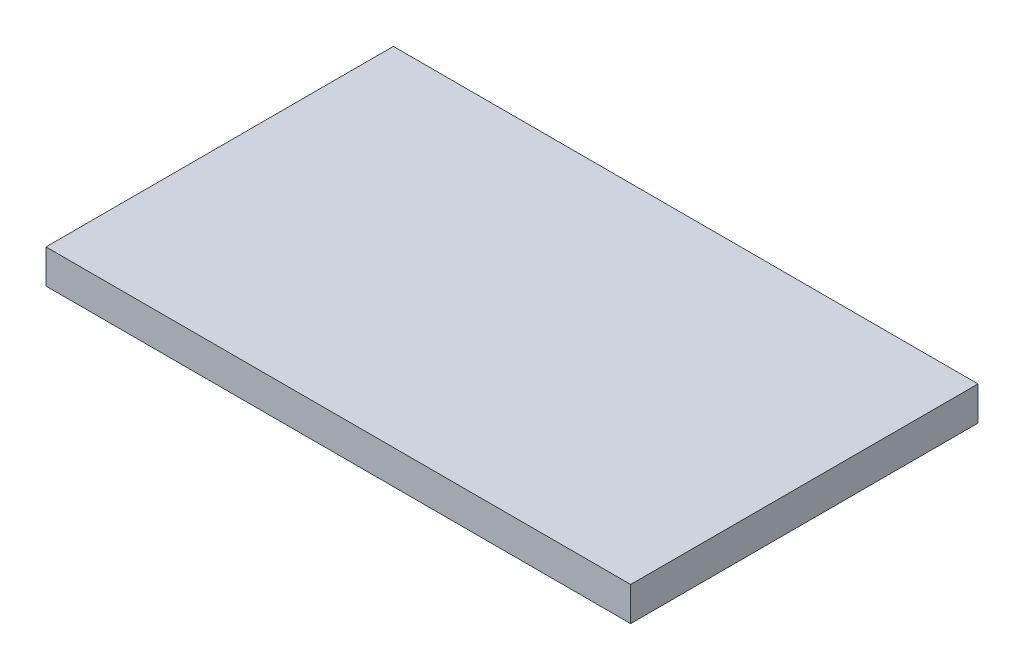
SolidWorks part; units mm, degrees
ref_plane "Front Plane" through (0, 0, 0) normal (0, 0, 1) x (1, 0, 0)
ref_plane "Top Plane" through (0, 0, 0) normal (0, 1, 0) x (1, 0, 0)
ref_plane "Right Plane" through (0, 0, 0) normal (1, 0, 0) x (0, 0, -1)
other "Configuration Table"
sketch "Sketch1" plane through (0, 0, 0) normal (0, 0, 1) x (1, 0, 0)
  line L1 (62.5, 691) -> (1337.5, 691)
  line L2 (62.5, 691) -> (62.5, 765)
  line L3 (62.5, 765) -> (1337.5, 765)
  line L4 (1337.5, 691) -> (1337.5, 765)
extrude "STORE_ayirici_pu_1" add sketch "Sketch1" against normal blind 757.5 separate body
